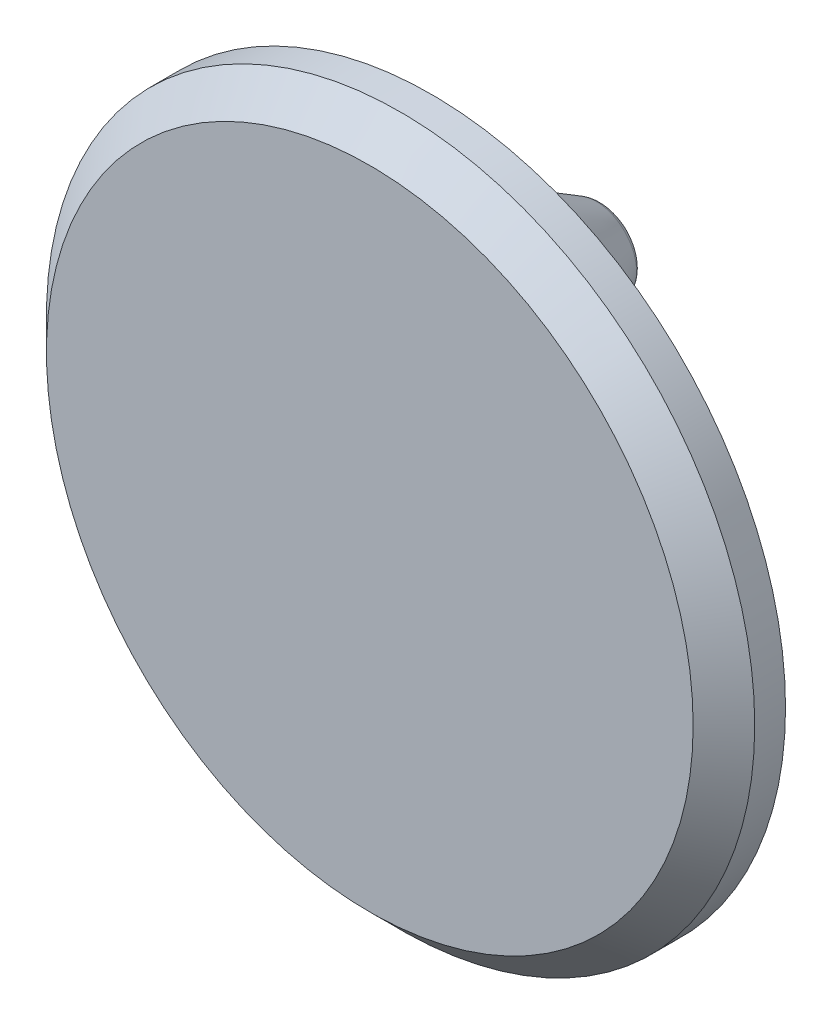
SolidWorks part; units mm, degrees
material "PLA"
ref_plane "Front Plane" through (0, 0, 0) normal (0, 0, 1) x (1, 0, 0)
ref_plane "Top Plane" through (0, 0, 0) normal (0, 1, 0) x (1, 0, 0)
ref_plane "Right Plane" through (0, 0, 0) normal (1, 0, 0) x (0, 0, -1)
sketch "Sketch1" plane through (0, 0, 0) normal (0, 0, 1) x (1, 0, 0)
  circle A0 centre (0, 0) radius 11.5
  dimension "D1" = 23
extrude "Boss-Extrude1" add sketch "Sketch1" along normal blind 2 contours A0
sketch "Sketch3" plane through (0, 0, 0) normal (1, 0, 0) x (0, 0, -1)
  line L0 (0, 4.5) -> (0, 6.9)
  line L1 (0, 6.9) -> (2.6, 6.9)
  line L2 (2.6, 6.9) -> (2.6, 7.4)
  line L3 (2.6, 7.4) -> (5.6, 5.6679)
  line L4 (5.6, 5.6679) -> (5.6, 4.5)
  line L5 (5.6, 4.5) -> (0, 4.5)
  line L6 (0, 4.5) -> (8.3842, 4.5) construction
  line L7 (0, -11.5) -> (0, 11.5) construction
  dimension "D1" = 7
  dimension "D3" = 4.8
  dimension "D5" = 60
  dimension "D6" = 3
  dimension "D7" = 2.6
  dimension "D2" = 5.8
revolve "Revolve1" add sketch "Sketch3" angle 360 about L6
sketch "Sketch4" plane through (0, 0, 0) normal (1, 0, 0) x (0, 0, -1)
  line L0 (5.6, 3.3321) -> (5.6, 5.6679) construction
  line L1 (5.6, 2.75) -> (0, 2.75)
  line L2 (5.6, 2.75) -> (5.6, 6.25)
  line L3 (5.6, 6.25) -> (0, 6.25)
  line L4 (0, 2.75) -> (0, 6.25)
  line L5 (0, 2.1) -> (0, 6.9) construction
  point P5 (5.6, 4.5)
  dimension "D1" = 3.5
extrude "Cut-Extrude1" [suppressed] cut sketch "Sketch4" against normal through all both and the other way through all
fillet "Fillet1" [suppressed] radius 1
chamfer "Chamfer1" distance 1 angle 45 1 edges at (11.5, 0, 2)
fillet "Fillet2" radius 0.5 1 edges at (0, 3.3321, -5.6)
other "Freeze***"
equation "\"shaft_diameter\"= 4.8"
equation "\"D3@Sketch3\"=\"shaft_diameter\""
equation "\"shaft_length\"= 2.6"
equation "\"D7@Sketch3\"=\"shaft_length\""
